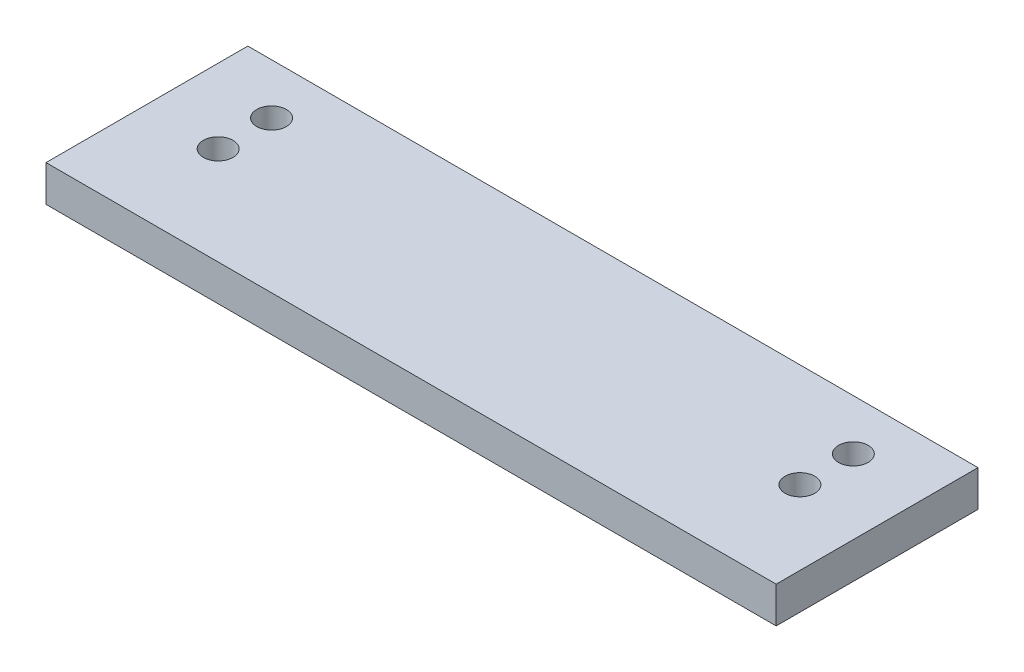
SolidWorks part; units mm, degrees
ref_plane "Front Plane" through (0, 0, 0) normal (0, 0, 1) x (1, 0, 0)
ref_plane "Top Plane" through (0, 0, 0) normal (0, 1, 0) x (1, 0, 0)
ref_plane "Right Plane" through (0, 0, 0) normal (1, 0, 0) x (0, 0, -1)
sketch "Sketch3" plane through (0, 0, 0) normal (0, 1, 0) x (1, 0, 0)
  line L1 (0, 0) -> (61.5, 0)
  line L2 (0, 0) -> (0, 17)
  line L3 (0, 17) -> (61.5, 17)
  line L4 (61.5, 0) -> (61.5, 17)
  dimension "D1" = 17
  dimension "D2" = 61.5
extrude "Boss-Extrude1" add sketch "Sketch3" along normal blind 3.05
sketch "Sketch4" plane through (0, 3.05, 0) normal (0, 1, 0) x (1, 0, 0)
  line L0 (6.25, 12.75) -> (6.25, 8.25)
  line L1 (0, 17) -> (6.25, 17)
  line L2 (0, 17) -> (0, 12.75)
  line L3 (0, 12.75) -> (6.25, 12.75)
  line L4 (6.25, 17) -> (6.25, 12.75)
  line L5 (0, 12.0139) -> (3.05, 12.0139)
  line L6 (0, 17) -> (0, 0) construction
  line L7 (55.25, 12.75) -> (55.25, 8.25)
  line L8 (61.5, 17) -> (55.25, 17)
  line L9 (61.5, 17) -> (61.5, 12.75)
  line L10 (61.5, 12.75) -> (55.25, 12.75)
  line L11 (55.25, 17) -> (55.25, 12.75)
  circle A0 centre (6.25, 12.75) radius 1.25
  circle A1 centre (6.25, 8.25) radius 1.25
  circle A2 centre (55.25, 12.75) radius 1.25
  circle A3 centre (55.25, 8.25) radius 1.25
  dimension "D3" = 2.5
  dimension "D6" = 2.5
  dimension "D9" = 2.5
  dimension "D11" = 2.5
  dimension "D1" = 4.25
  dimension "D2" = 6.25
  dimension "D4" = 4.5
  dimension "D5" = 3.05
  dimension "D7" = 6.25
  dimension "D8" = 4.25
  dimension "D10" = 4.5
extrude "Cut-Extrude1" cut sketch "Sketch4" against normal through all
